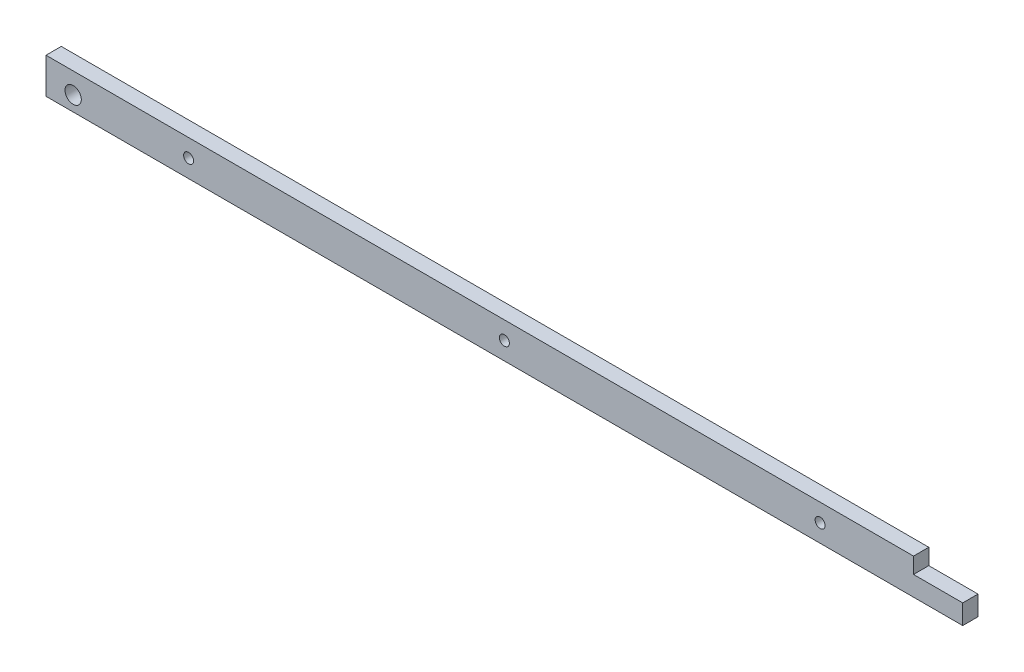
SolidWorks part; units mm, degrees
ref_plane "Front Plane" through (0, 0, 0) normal (0, 0, 1) x (1, 0, 0)
ref_plane "Top Plane" through (0, 0, 0) normal (0, 1, 0) x (1, 0, 0)
ref_plane "Right Plane" through (0, 0, 0) normal (1, 0, 0) x (0, 0, -1)
sketch "Sketch1" plane through (0, 0, 0) normal (0, 0, 1) x (1, 0, 0)
  line L0 (0, 12.9644) -> (432.66, 12.9644)
  line L1 (432.66, 12.9644) -> (432.66, 5.0194)
  line L2 (432.66, 5.0194) -> (457.2, 5.0194)
  line L3 (457.2, 5.0194) -> (457.2, -4.8006)
  line L5 (0, -4.8006) -> (0, 12.9644)
  line L6 (0, -4.8006) -> (457.2, -4.8006) construction
  line L7 (0, -4.8006) -> (457.2, -4.8006)
  line L8 (0, 16.1394) -> (457.2, 16.1394) construction
  line L9 (0, 16.1394) -> (457.2, 16.1394) construction
  circle A0 centre (386.08, 4.0819) radius 2.4892 construction
  circle A1 centre (228.6, 4.0819) radius 2.4892 construction
  circle A2 centre (71.12, 4.0819) radius 2.4892 construction
  circle A3 centre (386.08, 4.0819) radius 2.4892
  circle A4 centre (228.6, 4.0819) radius 2.4892
  circle A5 centre (71.12, 4.0819) radius 2.4892
  circle A6 centre (13.54, 2.5994) radius 4.0635
  point P21 (13.54, 29.6794)
  point P26 (13.54, 2.5994)
  dimension "D1" = 8.127
extrude "Boss-Extrude1" add sketch "Sketch1" along normal blind 7.62
